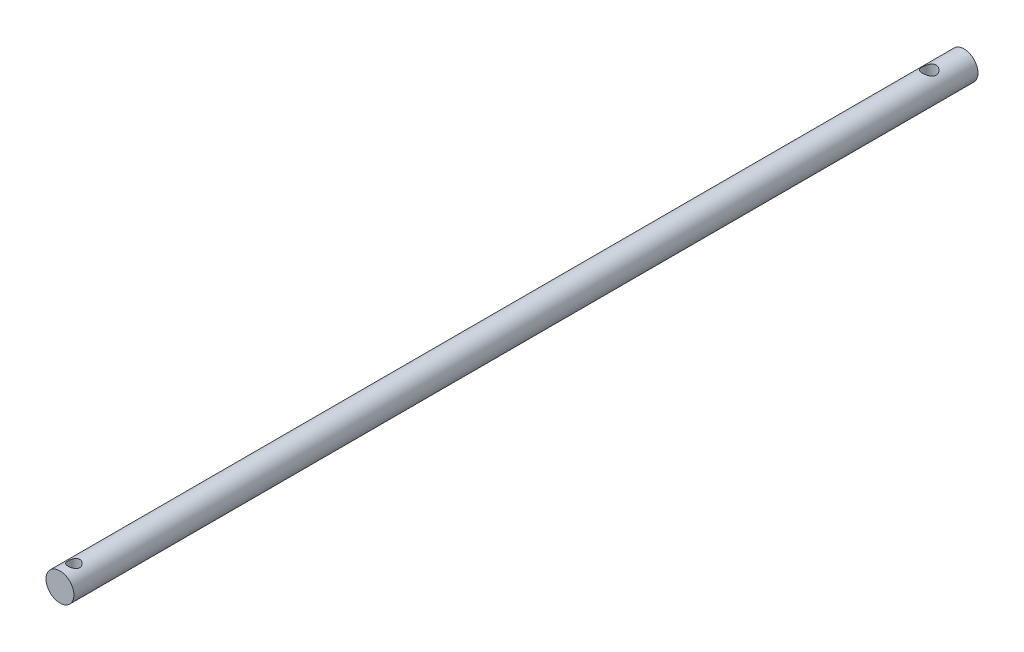
SolidWorks part; units mm, degrees
ref_plane "前视基准面" through (0, 0, 0) normal (0, 0, 1) x (1, 0, 0)
ref_plane "上视基准面" through (0, 0, 0) normal (0, 1, 0) x (1, 0, 0)
ref_plane "右视基准面" through (0, 0, 0) normal (1, 0, 0) x (0, 0, -1)
sketch "草图1" plane through (0, 0, 0) normal (0, 0, 1) x (1, 0, 0)
  circle A0 centre (0, 0) radius 4
  dimension "D1" = 8
extrude "拉伸1" add sketch "草图1" along normal blind 259
ref_plane "基准面1" through (0, 4, 0) normal (0, 1, 0) x (-1, 0, 0)
hole_wizard "M4 螺纹孔2" positions "草图6" profile "草图5" tap size "M4" standard "ISO"
sketch "草图6" plane through (0, 4, 0) normal (0, 1, 0) x (-1, 0, 0)
  line L0 (0, -1000) -> (0, 49000) construction
  line L2 (-4, 0) -> (4, 0) construction
  point P0 (0, 10)
  dimension "D1" = 10
sketch "草图5" plane through (0, 4, 10) normal (1, 0, 0) x (0, 0, 1)
  line L0 (0, 0) -> (0, 7.0914)
  line L1 (0, 7.0914) -> (1.65, 6.1)
  line L2 (1.65, 6.1) -> (1.65, 4)
  line L3 (1.65, 4) -> (2, 4)
  line L4 (2, 4) -> (2, 0)
  line L5 (2, 0) -> (0, 0)
  line L10 (0, 7.0914) -> (-1.65, 6.1) construction
  line L11 (0, -6.35) -> (0, 107.95) construction
  dimension "蹟恇謂郰芛眻噤" = 3.3
  dimension "蹟恇謂郰芛旮僅" = 6.1
  dimension "蹟恇翋眻噤" = 4
  dimension "蹟恇旮僅" = 4
  dimension "絳芛褒僅" = 118
sketch "草图7" plane through (0, 4, 0) normal (0, 1, 0) x (-1, 0, 0)
  line L0 (4, 259) -> (-4, 259) construction
  circle A0 centre (0, 255) radius 1.69
  dimension "D1" = 3.38
  dimension "D2" = 4
extrude "切除-拉伸1" cut sketch "草图7" against normal through all
